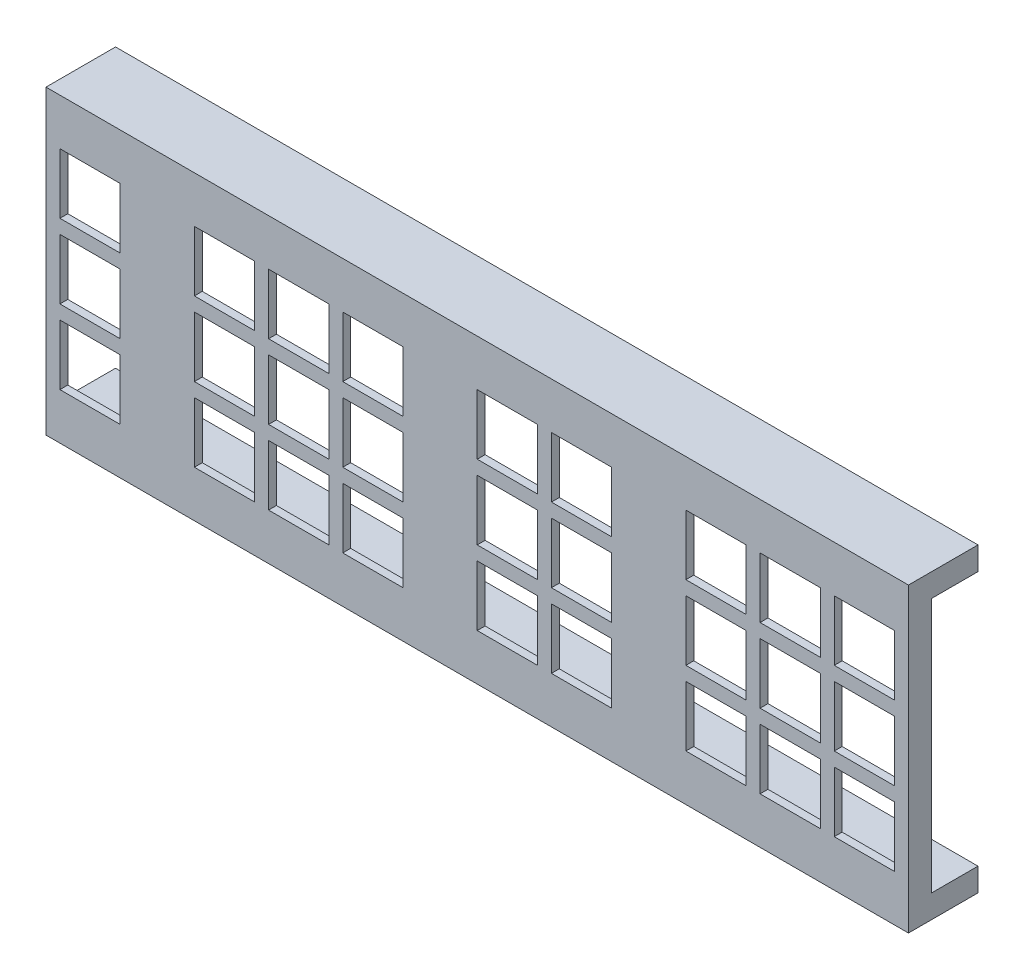
SolidWorks part; units mm, degrees
ref_plane "Plan de face" through (0, 0, 0) normal (0, 0, 1) x (1, 0, 0)
ref_plane "Plan de dessus" through (0, 0, 0) normal (0, 1, 0) x (1, 0, 0)
ref_plane "Plan de droite" through (0, 0, 0) normal (1, 0, 0) x (0, 0, -1)
sketch "Esquisse1" plane through (0, 0, 0) normal (0, 0, 1) x (1, 0, 0)
  line L1 (-93, -51) -> (93, -51)
  line L2 (-93, -51) -> (-93, 0)
  line L3 (-93, 0) -> (93, 0)
  line L4 (93, -51) -> (93, 0)
  line L13 (0, 49979.1071) -> (0, -49979.1071) construction
  point P0 (0, 0)
  point P16 (0, -51)
  point P17 (0, 0)
  point P27 (0, 0)
  dimension "D1" = 186
  dimension "D2" = 51
extrude "Boss.-Extru.1" add sketch "Esquisse1" along normal blind 35
sketch "Esquisse7" plane through (0, 0, 35) normal (0, 0, 1) x (1, 0, 0)
  line L0 (93, 0) -> (-93, 0) construction
  line L1 (-90, -3) -> (-77, -3)
  line L2 (-90, -3) -> (-90, -16)
  line L3 (-90, -16) -> (-77, -16)
  line L4 (-77, -3) -> (-77, -16)
  line L5 (-90, -3) -> (-77, -16) construction
  line L6 (-90, -16) -> (-77, -3) construction
  line L7 (-93, 0) -> (-93, -51) construction
  point P0 (-83.5, -9.5)
  dimension "D1" = 13
  dimension "D2" = 13
  dimension "D3" = 3
  dimension "D4" = 3
extrude "Enlèv. mat.-Extru.5" cut sketch "Esquisse7" against normal blind 91
pattern_linear "Répétition linéaire5" count 3 spacing 16 along (0, -1, 0) of "Enlèv. mat.-Extru.5"
sketch "Esquisse8" plane through (0, 0, 35) normal (0, 0, 1) x (1, 0, 0)
  line L0 (93, 0) -> (-93, 0) construction
  line L1 (-61, -3) -> (-48, -3)
  line L2 (-61, -3) -> (-61, -16)
  line L3 (-61, -16) -> (-48, -16)
  line L4 (-48, -3) -> (-48, -16)
  line L5 (-61, -3) -> (-48, -16) construction
  line L6 (-61, -16) -> (-48, -3) construction
  line L7 (-77, -16) -> (-77, -3) construction
  point P0 (-54.5, -9.5)
  dimension "D1" = 13
  dimension "D2" = 13
  dimension "D3" = 3
  dimension "D4" = 16
extrude "Enlèv. mat.-Extru.6" cut sketch "Esquisse8" against normal blind 103
pattern_linear "Répétition linéaire6" count 3 spacing 16 along (0, -1, 0) count 3 spacing 16 along (1, 0, 0) of "Enlèv. mat.-Extru.6"
sketch "Esquisse9" plane through (0, 0, 35) normal (0, 0, 1) x (1, 0, 0)
  line L0 (-16, -16) -> (-16, -3) construction
  line L1 (0, -3) -> (13, -3)
  line L2 (0, -3) -> (0, -16)
  line L3 (0, -16) -> (13, -16)
  line L4 (13, -3) -> (13, -16)
  line L5 (0, -3) -> (13, -16) construction
  line L6 (0, -16) -> (13, -3) construction
  line L7 (93, 0) -> (-93, 0) construction
  point P0 (6.5, -9.5)
  dimension "D1" = 13
  dimension "D2" = 13
  dimension "D3" = 16
  dimension "D4" = 3
extrude "Enlèv. mat.-Extru.7" cut sketch "Esquisse9" against normal blind 77
pattern_linear "Répétition linéaire7" count 3 spacing 16 along (0, -1, 0) count 2 spacing 16 along (1, 0, 0) of "Enlèv. mat.-Extru.7"
sketch "Esquisse10" plane through (0, 0, 35) normal (0, 0, 1) x (1, 0, 0)
  line L0 (29, -16) -> (29, -3) construction
  line L1 (45, -3) -> (58, -3)
  line L2 (45, -3) -> (45, -16)
  line L3 (45, -16) -> (58, -16)
  line L4 (58, -3) -> (58, -16)
  line L5 (45, -3) -> (58, -16) construction
  line L6 (45, -16) -> (58, -3) construction
  line L7 (93, 0) -> (-93, 0) construction
  point P0 (51.5, -9.5)
  dimension "D1" = 13
  dimension "D2" = 13
  dimension "D3" = 16
  dimension "D4" = 3
extrude "Enlèv. mat.-Extru.8" cut sketch "Esquisse10" against normal blind 78
pattern_linear "Répétition linéaire8" count 3 spacing 16 along (1, 0, 0) count 3 spacing 16 along (0, -1, 0) of "Enlèv. mat.-Extru.8"
sketch "Esquisse14" plane through (0, -51, 0) normal (0, -1, 0) x (1, 0, 0)
  line L0 (0, 0) -> (-15.3262, 0) construction
  line L1 (-12.6631, 0) -> (-2.6631, 0)
  line L2 (-12.6631, 0) -> (-12.6631, 5)
  line L3 (-12.6631, 5) -> (-2.6631, 5)
  line L4 (-2.6631, 0) -> (-2.6631, 5)
  line L5 (-12.6631, 0) -> (-2.6631, 5) construction
  line L6 (-12.6631, 5) -> (-2.6631, 0) construction
  line L7 (-93, 0) -> (93, 0) construction
  point P0 (-7.6631, 2.5)
  point P5 (-15.3262, 0)
  point P6 (0, 0)
  point P10 (0, 0)
  point P12 (-7.6631, 0)
  point P13 (-7.6631, 0)
  dimension "D1" = 10
  dimension "D2" = 5
extrude "Boss.-Extru.3" add sketch "Esquisse14" along normal blind 7
sketch "Esquisse25" plane through (0, 0, 0) normal (0, 1, 0) x (1, 0, 0)
  line L1 (-93, 0) -> (93, 0)
  line L2 (-93, 0) -> (-93, -35)
  line L3 (-93, -35) -> (93, -35)
  line L4 (93, 0) -> (93, -35)
extrude "Boss.-Extru.7" add sketch "Esquisse25" along normal blind 7
sketch "Esquisse18" plane through (0, -51, 0) normal (0, -1, 0) x (1, 0, 0)
  line L0 (-93, 0) -> (93, 0)
  line L2 (93, 0) -> (93, 35)
  line L3 (93, 35) -> (-93, 35)
  line L4 (-93, 35) -> (-93, 0)
extrude "Boss.-Extru.5" add sketch "Esquisse18" along normal blind 7
sketch "Esquisse16" plane through (-93, 0, 0) normal (-1, 0, 0) x (0, 0, 1)
  line L0 (35, -58) -> (0, -58) construction
  line L3 (33.3, -53) -> (30, -53)
  line L4 (30, -53) -> (30, 2)
  line L5 (30, 2) -> (33.3, 2)
  line L6 (33.3, 2) -> (33.3, -53)
  line L8 (0, 7) -> (35, 7) construction
  point P1 (31.65, -53)
  dimension "D1" = 5
  dimension "D4" = 5
  dimension "D5" = 3.3
extrude "Enlèv. mat.-Extru.11" cut sketch "Esquisse16" against normal blind 184
sketch "Esquisse15" plane through (0, 0, 0) normal (0, 0, -1) x (-1, 0, 0)
  circle A0 centre (8.4823, -42.4466) radius 1
  circle A1 centre (8.4823, -9.749) radius 1
  circle A2 centre (68.823, -42.4466) radius 1
  circle A3 centre (68.823, -9.749) radius 1
  circle A4 centre (-37.1355, -42.4466) radius 1
  circle A5 centre (-39.2159, -11.2606) radius 1
  dimension "D1" = 2
  dimension "D2" = 2
  dimension "D3" = 2
  dimension "D4" = 2
  dimension "D5" = 2
  dimension "D6" = 2
extrude "Enlèv. mat.-Extru.10" cut sketch "Esquisse15" against normal blind 7
sketch "Esquisse24" plane through (0, 0, 0) normal (0, 0, -1) x (-1, 0, 0)
  line L0 (77, -48) -> (90, -48) construction
  line L1 (88.5, -48) -> (78.5, -48)
  line L2 (88.5, -48) -> (88.5, -50)
  line L3 (88.5, -50) -> (78.5, -50)
  line L4 (78.5, -48) -> (78.5, -50)
  line L5 (48, -48) -> (61, -48) construction
  line L6 (59.5, -48) -> (49.5, -48)
  line L7 (59.5, -48) -> (59.5, -50)
  line L8 (59.5, -50) -> (49.5, -50)
  line L9 (49.5, -48) -> (49.5, -50)
  line L10 (32, -48) -> (45, -48) construction
  line L11 (43.5, -48) -> (33.5, -48)
  line L12 (43.5, -48) -> (43.5, -50)
  line L13 (43.5, -50) -> (33.5, -50)
  line L14 (33.5, -48) -> (33.5, -50)
  line L15 (16, -48) -> (29, -48) construction
  line L16 (27.5, -48) -> (17.5, -48)
  line L17 (27.5, -48) -> (27.5, -50)
  line L18 (27.5, -50) -> (17.5, -50)
  line L19 (17.5, -48) -> (17.5, -50)
  line L20 (-13, -48) -> (0, -48) construction
  line L21 (-1.5, -48) -> (-11.5, -48)
  line L22 (-1.5, -48) -> (-1.5, -50)
  line L23 (-1.5, -50) -> (-11.5, -50)
  line L24 (-11.5, -48) -> (-11.5, -50)
  line L25 (-29, -48) -> (-16, -48) construction
  line L26 (-17.5, -48) -> (-27.5, -48)
  line L27 (-17.5, -48) -> (-17.5, -50)
  line L28 (-17.5, -50) -> (-27.5, -50)
  line L29 (-27.5, -48) -> (-27.5, -50)
  line L30 (-58, -48) -> (-45, -48) construction
  line L31 (-46.5, -48) -> (-56.5, -48)
  line L32 (-46.5, -48) -> (-46.5, -50)
  line L33 (-46.5, -50) -> (-56.5, -50)
  line L34 (-56.5, -48) -> (-56.5, -50)
  line L35 (-74, -48) -> (-61, -48) construction
  line L36 (-62.5, -48) -> (-72.5, -48)
  line L37 (-62.5, -48) -> (-62.5, -50)
  line L38 (-62.5, -50) -> (-72.5, -50)
  line L39 (-72.5, -48) -> (-72.5, -50)
  line L40 (-90, -48) -> (-77, -48) construction
  line L41 (-78.5, -48) -> (-88.5, -48)
  line L42 (-78.5, -48) -> (-78.5, -50)
  line L43 (-78.5, -50) -> (-88.5, -50)
  line L44 (-88.5, -48) -> (-88.5, -50)
  line L45 (-77, -3) -> (-90, -3) construction
  line L46 (-78.5, -3) -> (-88.5, -3)
  line L47 (-78.5, -3) -> (-78.5, -1)
  line L48 (-78.5, -1) -> (-88.5, -1)
  line L49 (-88.5, -3) -> (-88.5, -1)
  line L50 (-61, -3) -> (-74, -3) construction
  line L51 (-62.5, -3) -> (-72.5, -3)
  line L52 (-62.5, -3) -> (-62.5, -1)
  line L53 (-62.5, -1) -> (-72.5, -1)
  line L54 (-72.5, -3) -> (-72.5, -1)
  line L55 (-45, -3) -> (-58, -3) construction
  line L56 (-46.5, -3) -> (-56.5, -3)
  line L57 (-46.5, -3) -> (-46.5, -1)
  line L58 (-46.5, -1) -> (-56.5, -1)
  line L59 (-56.5, -3) -> (-56.5, -1)
  line L60 (-16, -3) -> (-29, -3) construction
  line L61 (-17.5, -3) -> (-27.5, -3)
  line L62 (-17.5, -3) -> (-17.5, -1)
  line L63 (-17.5, -1) -> (-27.5, -1)
  line L64 (-27.5, -3) -> (-27.5, -1)
  line L65 (0, -3) -> (-13, -3) construction
  line L66 (-1.5, -3) -> (-11.5, -3)
  line L67 (-1.5, -3) -> (-1.5, -1)
  line L68 (-1.5, -1) -> (-11.5, -1)
  line L69 (-11.5, -3) -> (-11.5, -1)
  line L70 (29, -3) -> (16, -3) construction
  line L71 (17.5, -3) -> (27.5, -3)
  line L72 (17.5, -3) -> (17.5, -1)
  line L73 (17.5, -1) -> (27.5, -1)
  line L74 (27.5, -3) -> (27.5, -1)
  line L75 (45, -3) -> (32, -3) construction
  line L76 (33.5, -3) -> (43.5, -3)
  line L77 (33.5, -3) -> (33.5, -1)
  line L78 (33.5, -1) -> (43.5, -1)
  line L79 (43.5, -3) -> (43.5, -1)
  line L80 (61, -3) -> (48, -3) construction
  line L81 (49.5, -3) -> (59.5, -3)
  line L82 (49.5, -3) -> (49.5, -1)
  line L83 (49.5, -1) -> (59.5, -1)
  line L84 (59.5, -3) -> (59.5, -1)
  line L85 (90, -3) -> (77, -3) construction
  line L86 (78.5, -3) -> (88.5, -3)
  line L87 (78.5, -3) -> (78.5, -1)
  line L88 (78.5, -1) -> (88.5, -1)
  line L89 (88.5, -3) -> (88.5, -1)
  point P108 (83.5, -48)
  point P109 (54.5, -48)
  point P110 (38.5, -48)
  point P111 (22.5, -48)
  point P112 (-6.5, -48)
  point P113 (-22.5, -48)
  point P114 (-51.5, -48)
  point P115 (-67.5, -48)
  point P116 (-83.5, -48)
  point P117 (-83.5, -3)
  point P118 (-67.5, -3)
  point P119 (-51.5, -3)
  point P120 (-22.5, -3)
  point P121 (-6.5, -3)
  point P122 (22.5, -3)
  point P123 (38.5, -3)
  point P124 (54.5, -3)
  point P125 (83.5, -3)
  point P126 (83.5, -3)
  point P128 (54.5, -3)
  point P130 (38.5, -3)
  point P132 (22.5, -3)
  point P134 (-6.5, -3)
  point P136 (-22.5, -3)
  point P138 (-51.5, -3)
  point P140 (-67.5, -3)
  point P143 (-83.5, -3)
  point P145 (-83.5, -48)
  point P148 (-51.5, -48)
  point P150 (-22.5, -48)
  point P152 (-6.5, -48)
  point P154 (22.5, -48)
  point P156 (38.5, -48)
  point P159 (54.5, -48)
  point P161 (83.5, -48)
  dimension "D1" = 10
  dimension "D2" = 10
  dimension "D3" = 10
  dimension "D4" = 10
  dimension "D5" = 10
  dimension "D6" = 10
  dimension "D7" = 10
  dimension "D8" = 10
  dimension "D9" = 10
  dimension "D10" = 10
  dimension "D11" = 10
  dimension "D12" = 10
  dimension "D13" = 10
  dimension "D14" = 10
  dimension "D15" = 10
  dimension "D16" = 10
  dimension "D17" = 10
  dimension "D18" = 10
  dimension "D19" = 2
  dimension "D20" = 2
  dimension "D21" = 2
  dimension "D22" = 2
  dimension "D23" = 2
  dimension "D24" = 2
  dimension "D25" = 2
  dimension "D26" = 2
  dimension "D27" = 2
  dimension "D28" = 2
  dimension "D29" = 2
  dimension "D30" = 2
  dimension "D31" = 2
  dimension "D32" = 2
  dimension "D33" = 2
  dimension "D34" = 2
  dimension "D35" = 2
  dimension "D36" = 2
extrude "Enlèv. mat.-Extru.12" cut sketch "Esquisse24" against normal blind 1
sketch "Esquisse19" plane through (0, 0, 0) normal (0, 0, -1) x (-1, 0, 0)
  line L0 (-93, -58) -> (-93, 7) construction
  line L1 (93, -58) -> (-93, -58)
  line L2 (93, -58) -> (93, -57)
  line L3 (93, -57) -> (-93, -57)
  line L4 (-93, -58) -> (-93, -57)
  line L5 (93, 7) -> (93, -58) construction
  line L6 (-93, 7) -> (93, 7)
  line L7 (-93, 7) -> (-93, 6)
  line L8 (-93, 6) -> (93, 6)
  line L9 (93, 7) -> (93, 6)
  line L11 (-93, -57) -> (-92, -57)
  line L12 (-93, -57) -> (-93, 6)
  line L13 (-93, 6) -> (-92, 6)
  line L14 (-92, -57) -> (-92, 6)
  line L15 (93, 6) -> (92, 6)
  line L16 (93, 6) -> (93, -57)
  line L17 (93, -57) -> (92, -57)
  line L18 (92, 6) -> (92, -57)
  dimension "D1" = 1
  dimension "D2" = 1
  dimension "D3" = 1
  dimension "D4" = 1
extrude "Boss.-Extru.8" add sketch "Esquisse19" along normal blind 30 contours L4 L1 L2 L3 | L8 L18 L3 L16 | L9 L6 L7 L8 | L3 L14 L8 L12
sketch "Esquisse26" plane through (-93, 0, 0) normal (-1, 0, 0) x (0, 0, 1)
  line L0 (-30, -58) -> (2.5, 7) construction
  line L1 (-30, 7) -> (35, 7) construction
  line L2 (-30, 7) -> (2.5, -58) construction
  line L3 (35, -58) -> (-30, -58) construction
  circle A0 centre (-13.75, -25.5) radius 1.75
  dimension "D1" = 3.5
extrude "Enlèv. mat.-Extru.14" cut sketch "Esquisse26" against normal blind 30
sketch "Esquisse27" plane through (-93, 0, 0) normal (-1, 0, 0) x (0, 0, 1)
  line L0 (30, 2) -> (20, 2)
  line L1 (20, 2) -> (20, 7)
  line L2 (-30, 7) -> (35, 7) construction
  line L3 (20, 7) -> (35, 7)
  line L4 (35, 7) -> (35, -58)
  line L5 (35, -58) -> (20, -58)
  line L6 (35, -58) -> (-30, -58) construction
  line L7 (30, -53) -> (20, -53)
  line L8 (20, -53) -> (20, -58)
  line L9 (30, -53) -> (30, 2)
  circle M8 centre (-13.75, -25.5) radius 1.75
  line M12 (30, -53) -> (30, 2)
  line M13 (35, 7) -> (-30, 7)
  line M14 (-30, 7) -> (-30, -58)
  line M15 (-30, -58) -> (35, -58)
  dimension "D1" = 10
  dimension "D2" = 10
extrude "Enlèv. mat.-Extru.20" cut sketch "Esquisse27" against normal through all contours L8 L7 L0 L1 M12 M13 M14 M15 M8 | M8
